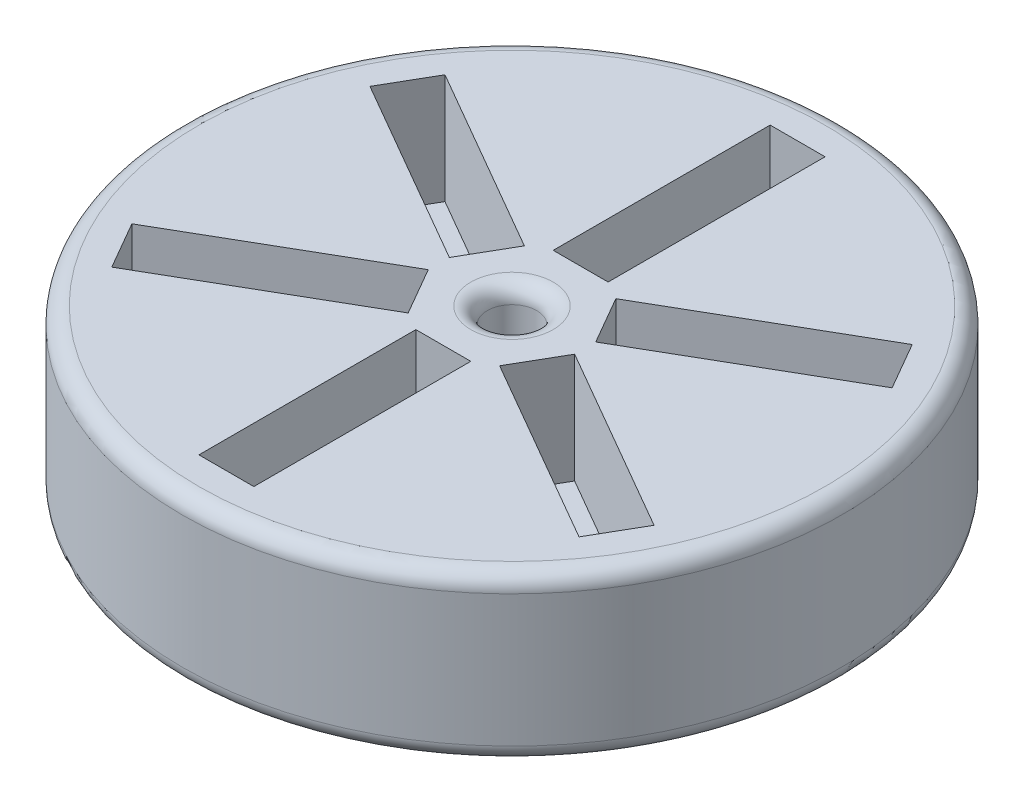
SolidWorks part; units mm, degrees
ref_plane "Front Plane" through (0, 0, 0) normal (0, 0, 1) x (1, 0, 0)
ref_plane "Top Plane" through (0, 0, 0) normal (0, 1, 0) x (1, 0, 0)
ref_plane "Right Plane" through (0, 0, 0) normal (1, 0, 0) x (0, 0, -1)
sketch "Sketch2" plane through (0, 0, 0) normal (0, 1, 0) x (1, 0, 0)
  circle A0 centre (0, 0) radius 30
  dimension "D1" = 60
extrude "Boss-Extrude1" add sketch "Sketch2" along normal blind 15
sketch "Sketch3" plane through (0, 15, 0) normal (0, 1, 0) x (1, 0, 0)
  circle A0 centre (0, 0) radius 2.25
  dimension "D1" = 4.5
extrude "Cut-Extrude1" cut sketch "Sketch3" against normal blind 9
fillet "Fillet1" radius 1.5 3 edges at (0, 15, 2.25) (0, 0, 30) (0, 15, 30)
sketch "Sketch4" plane through (0, 0, 0) normal (0, -1, 0) x (1, 0, 0)
  line L0 (-0.5, 24.5) -> (-0.5, -27.5)
  line L1 (-0.5, -27.5) -> (0.5, -27.5)
  line L2 (0.5, -27.5) -> (0.5, 24.5)
  line L3 (0.5, 24.5) -> (3, 24.5)
  line L4 (3, 24.5) -> (0, 27.5)
  line L5 (0, 27.5) -> (-3, 24.5)
  line L6 (-3, 24.5) -> (-0.5, 24.5)
  line L7 (0, 27.5) -> (0, -27.5) construction
  line L8 (0, -27.5) -> (0, -28.5) construction
  line L9 (0, 27.5) -> (0, 28.5) construction
  circle A0 centre (0, 0) radius 28.5 construction
  point P2 (2.9374, 25.4626)
  dimension "D2" = 1
  dimension "D1" = 1
  dimension "D3" = 1
  dimension "D4" = 2.5
extrude "Cut-Extrude2" cut sketch "Sketch4" against normal blind 1
sketch "Sketch5" plane through (0, 15, 0) normal (0, 1, 0) x (1, 0, 0)
  line L0 (0, 6.25) -> (0, 3.75) construction
  line L1 (-2.5, 26) -> (2.5, 26)
  line L2 (-2.5, 26) -> (-2.5, 6.25)
  line L3 (-2.5, 6.25) -> (2.5, 6.25)
  line L4 (2.5, 26) -> (2.5, 6.25)
  line L5 (-2.5, 26) -> (2.5, 6.25) construction
  line L6 (-2.5, 6.25) -> (2.5, 26) construction
  line L7 (0, 26) -> (0, 28.5) construction
  circle A0 centre (0, 0) radius 3.75 construction
  circle A1 centre (0, 0) radius 28.5 construction
  point P0 (0, 16.125)
  dimension "D1" = 2.5
  dimension "D2" = 2.5
  dimension "D3" = 5
extrude "Cut-Extrude3" cut sketch "Sketch5" against normal blind 10
pattern_circular "CirPattern1" count 6 over 360 about axis through (0, 0, 0) along (0, 1, 0) of "Cut-Extrude3"
